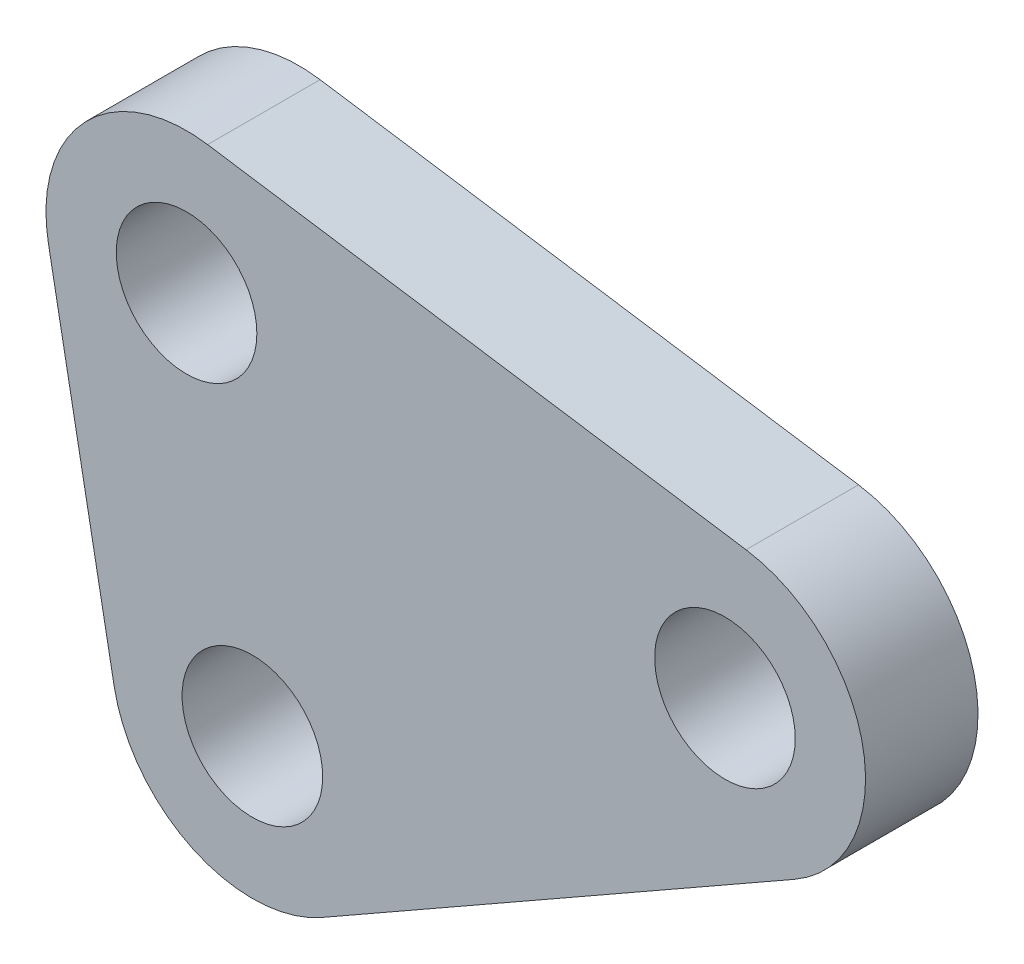
SolidWorks part; units mm, degrees
ref_plane "Front Plane" through (0, 0, 0) normal (0, 0, 1) x (1, 0, 0)
ref_plane "Top Plane" through (0, 0, 0) normal (0, 1, 0) x (1, 0, 0)
ref_plane "Right Plane" through (0, 0, 0) normal (1, 0, 0) x (0, 0, -1)
sketch "Sketch1" plane through (0, 0, 0) normal (0, 0, 1) x (1, 0, 0)
  line L0 (143.3333, 493) -> (716.6667, 493) construction
  line L6 (26.1417, 72.0991) -> (28.4826, 59.6183) construction
  line L7 (26.8916, 77.0426) -> (46.038, 74.1382)
  line L8 (30.958, 55.2742) -> (47.7636, 64.8506)
  line L9 (21.2274, 71.1774) -> (23.5682, 58.6966)
  circle A3 centre (26.1417, 72.0991) radius 2.5
  circle A4 centre (28.4826, 59.6183) radius 2.5
  circle A5 centre (45.2881, 69.1948) radius 2.5
  arc A13 (47.7636, 64.8506) -> (46.038, 74.1382) centre (45.2881, 69.1948) ccw
  arc A14 (26.8916, 77.0426) -> (21.2274, 71.1774) centre (26.1417, 72.0991) ccw
  arc A15 (23.5682, 58.6966) -> (30.958, 55.2742) centre (28.4826, 59.6183) ccw
extrude "Boss-Extrude1" add sketch "Sketch1" along normal blind 4
